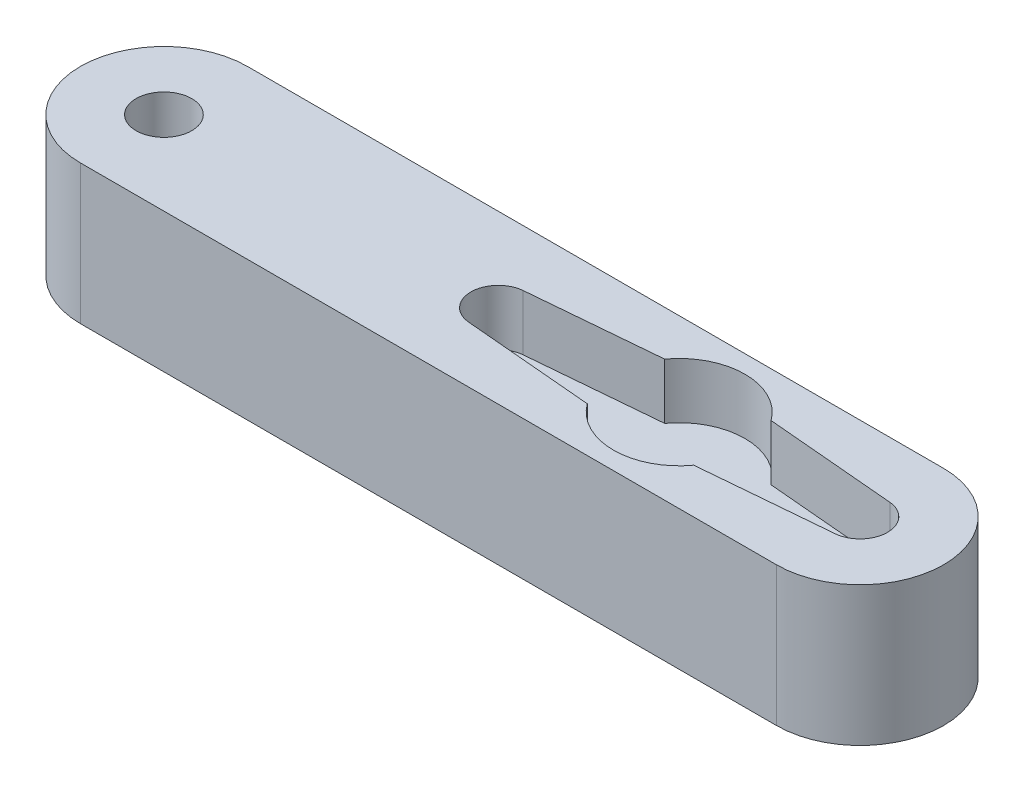
SolidWorks part; units mm, degrees
ref_plane "Front Plane" through (0, 0, 0) normal (0, 0, 1) x (1, 0, 0)
ref_plane "Top Plane" through (0, 0, 0) normal (0, 1, 0) x (1, 0, 0)
ref_plane "Right Plane" through (0, 0, 0) normal (1, 0, 0) x (0, 0, -1)
sketch "Sketch3" plane through (0, 0, 0) normal (0, 1, 0) x (1, 0, 0)
  line L0 (-31.75, 0) -> (31.75, 0) construction
  line L1 (-6.985, 0) -> (6.985, 0) construction
  line L2 (-31.75, 7.62) -> (31.75, 7.62)
  line L3 (-31.75, -7.62) -> (31.75, -7.62)
  arc A0 (-31.75, 7.62) -> (-31.75, -7.62) centre (-31.75, 0) ccw
  arc A1 (31.75, -7.62) -> (31.75, 7.62) centre (31.75, 0) ccw
  point P5 (0, 0)
  point P10 (0, 0)
  point P11 (0, 0)
  point P12 (0, 0)
  point P13 (38.1, 0)
  point P14 (0, 0)
  dimension "D2" = 7.62
  dimension "D1" = 63.5
  dimension "D3" = 31.75
extrude "Boss-Extrude1" add sketch "Sketch3" along normal blind 12.7
sketch "Sketch4" plane through (0, 12.7, 0) normal (0, 1, 0) x (1, 0, 0)
  circle A0 centre (-31.75, 0) radius 2.54
  dimension "D1" = 5.08
extrude "Cut-Extrude3" cut sketch "Sketch4" against normal through all
sketch "Sketch9" plane through (0, 12.7, 0) normal (0, 1, 0) x (-1, 0, 0)
  line L0 (-31.75, 0) -> (1.25, 0) construction
  line L1 (1.4679, -2.4905) -> (-10.3972, -3.5286)
  line L6 (1.4679, 2.4905) -> (-10.3972, 3.5286)
  line L9 (-15.25, 6) -> (-15.25, -6) construction
  line L12 (-31.9679, 2.4905) -> (-20.1028, 3.5286)
  line L13 (-31.9679, -2.4905) -> (-20.1028, -3.5286)
  circle A2 centre (-15.25, 0) radius 2.54 construction
  arc A9 (-10.3972, 3.5286) -> (-20.1028, 3.5286) centre (-15.25, 0) ccw
  arc A10 (1.4679, -2.4905) -> (1.4679, 2.4905) centre (1.25, 0) ccw
  arc A16 (-20.1028, -3.5286) -> (-10.3972, -3.5286) centre (-15.25, 0) ccw
  arc A22 (-31.9679, -2.4905) -> (-31.9679, 2.4905) centre (-31.75, 0) cw
  point P9 (-15.25, 0)
  dimension "D2" = 33
  dimension "D12" = 12
  dimension "D13" = 2.5
  dimension "D3" = 5.08
  dimension "D14" = 5
  dimension "D15" = 5
extrude "Cut-Extrude6" cut sketch "Sketch9" against normal blind 5.08 contours L12 A9 L6 A10 L1 A16 L13 A22
equation "\"TibiaLength\"= 5in"
equation "\"TibiaRadius\"= 0.3in"
equation "\"TibiaDistFromCentre\"= \"TibiaLength\" / 2"
equation "\"TibiaThickness\"= 0.5in"
equation "\"HoleRadius\"= 0.2in"
equation "\"D1@Sketch3\"=\"TibiaLength\"/2"
equation "\"D2@Sketch3\"= \"TibiaRadius\""
equation "\"D3@Sketch3\"=\"TibiaDistFromCentre\"/2"
equation "\"D1@Boss-Extrude1\"= \"TibiaThickness\""
equation "\"D1@Sketch4\"= \"HoleRadius\""
